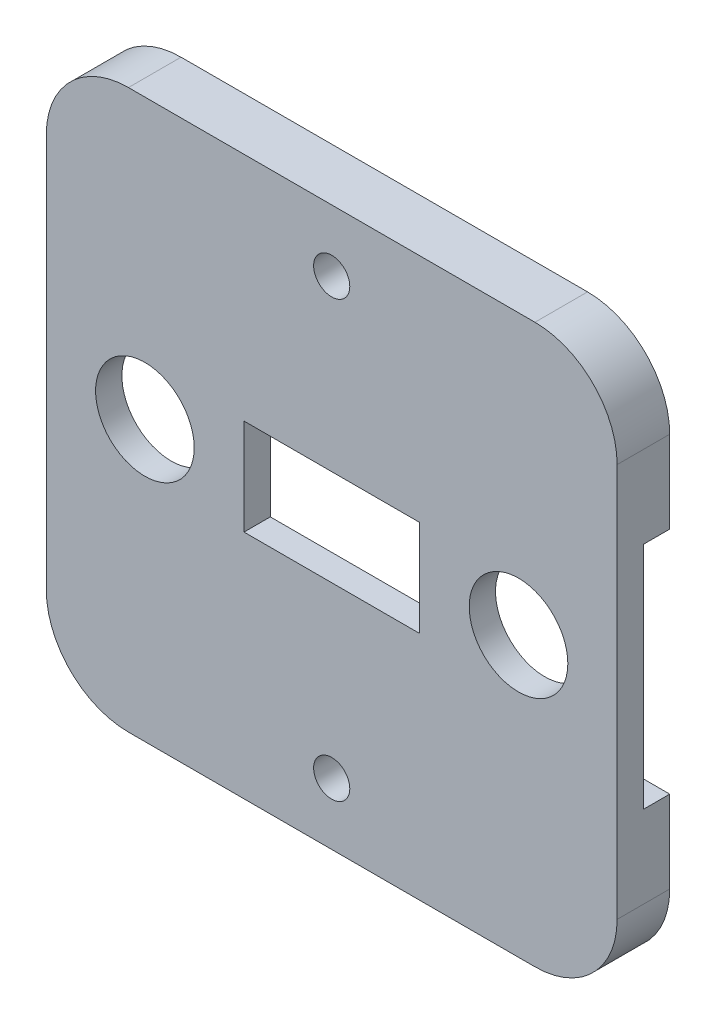
SolidWorks part; units mm, degrees
ref_plane "Front Plane" through (0, 0, 0) normal (0, 0, 1) x (1, 0, 0)
ref_plane "Top Plane" through (0, 0, 0) normal (0, 1, 0) x (1, 0, 0)
ref_plane "Right Plane" through (0, 0, 0) normal (1, 0, 0) x (0, 0, -1)
sketch "Sketch1" plane through (0, 0, 0) normal (0, 0, 1) x (1, 0, 0)
  line L1 (-22.0535, -18.6229) -> (-22.0535, -12.2729)
  line L2 (-15.7035, -5.9229) -> (15.7036, -5.9229)
  line L51 (-9.4424, -18.6229) -> (21.5953, -18.6229)
  line L52 (-22.0535, -18.6229) -> (22.0536, -18.6229) construction
  line L54 (-9.4424, -36.3521) -> (21.5953, -36.3521)
  line L55 (-22.0535, -36.3521) -> (22.0536, -36.3521) construction
  line L56 (-22.0535, -36.3521) -> (22.0536, -36.3521)
  line L57 (-22.0535, -36.3521) -> (-22.0535, -42.7021)
  line L58 (-15.7035, -49.0521) -> (15.7036, -49.0521)
  line L59 (22.0536, -36.3521) -> (22.0536, -42.7021)
  line L60 (22.0536, -18.6229) -> (-22.0535, -18.6229)
  line L61 (22.0536, -18.6229) -> (22.0536, -12.2729)
  circle A0 centre (-14.4335, -27.4875) radius 1.319 construction
  circle A1 centre (14.4336, -27.4875) radius 1.319 construction
  circle A2 centre (-14.4335, -27.4875) radius 1.319 construction
  circle A3 centre (14.4336, -27.4875) radius 1.319 construction
  arc A8 (-15.7035, -49.0521) -> (-22.0535, -42.7021) centre (-15.7035, -42.7021) cw
  arc A9 (15.7036, -49.0521) -> (22.0536, -42.7021) centre (15.7036, -42.7021) ccw
  arc A10 (15.7036, -5.9229) -> (22.0536, -12.2729) centre (15.7036, -12.2729) cw
  arc A11 (-22.0535, -12.2729) -> (-15.7035, -5.9229) centre (-15.7035, -12.2729) cw
  point P3 (-22.0535, -49.0521)
  point P21 (-22.0535, -49.0521)
  dimension "D6" = 7.62
  dimension "D4" = 6.35
  dimension "D3" = 12.7
  dimension "D5" = 7.62
  dimension "D1" = 0.508
  dimension "D2" = 0.508
extrude "Boss-Extrude1" add sketch "Sketch1" along normal offset from surface (4.064 mm away) 2.54 contours L60 L1 A11 L2 A10 L61 | L58 A9 L59 L56 L57 A8
sketch "Sketch2" plane through (0, 0, 4.064) normal (0, 0, 1) x (1, 0, 0)
  line L0 (-6.0134, -30.2624) -> (-6.0134, -30.4402) construction
  line L1 (-22.0535, -39.5271) -> (22.0536, -39.5271)
  line L7 (22.0536, -15.4479) -> (-22.0535, -15.4479)
  line L9 (-6.0134, -30.2624) -> (-6.0134, -24.7125) construction
  line L10 (-6.0134, -24.5347) -> (-6.0134, -24.7125) construction
  line L11 (6.0135, -24.5347) -> (-6.0134, -24.5347) construction
  line L12 (6.0135, -30.4402) -> (6.0135, -24.5347) construction
  line L13 (-6.0134, -30.4402) -> (6.0135, -30.4402) construction
  line L14 (-6.0134, -30.2624) -> (-6.0134, -30.4402) construction
  line L15 (-6.0134, -30.2624) -> (-6.0134, -24.7125) construction
  line L16 (-6.0134, -24.5347) -> (-6.0134, -24.7125) construction
  line L17 (6.0135, -24.5347) -> (-6.0134, -24.5347) construction
  line L18 (6.0135, -30.4402) -> (6.0135, -24.5347) construction
  line L19 (-6.0134, -30.4402) -> (6.0135, -30.4402) construction
  line L20 (-6.7754, -23.7727) -> (-6.7754, -24.7125)
  line L21 (-6.7754, -30.2624) -> (-6.7754, -24.7125)
  line L26 (-6.7754, -30.2624) -> (-6.7754, -31.2022)
  line L27 (-6.7754, -31.2022) -> (6.7755, -31.2022)
  line L30 (6.7755, -31.2022) -> (6.7755, -23.7727)
  line L31 (6.7755, -23.7727) -> (-6.7754, -23.7727)
  line L32 (22.0536, -18.6229) -> (-22.0535, -18.6229) construction
  line L33 (-22.0535, -15.4479) -> (-22.0535, -39.5271)
  line L35 (22.0536, -39.5271) -> (22.0536, -15.4479)
  circle A0 centre (-14.4335, -27.4875) radius 1.397 construction
  circle A1 centre (14.4336, -27.4875) radius 1.397 construction
  circle A2 centre (-14.4335, -27.4875) radius 1.397 construction
  circle A3 centre (14.4336, -27.4875) radius 1.397 construction
  circle A4 centre (14.4336, -27.4875) radius 3.81
  circle A5 centre (-14.4335, -27.4875) radius 3.81
  arc A10 (9.4933, -23.6775) -> (9.4933, -31.2975) centre (9.4933, -27.4875) ccw construction
  point P37 (-6.0134, -27.4875)
  point P45 (-22.0535, -27.4875)
  dimension "D3" = 0.762
  dimension "D5" = 7.62
  dimension "D1" = 7.62
  dimension "D4" = 3.175
extrude "Boss-Extrude2" add sketch "Sketch2" against normal offset from surface (2.032 mm away) 0.508
sketch "Sketch3" plane through (0, 0, 4.064) normal (0, 0, 1) x (1, 0, 0)
  line L0 (0, -49.0521) -> (0, -44.2896) construction
  line L1 (0, -10.6854) -> (0, -5.9229) construction
  line L2 (-15.7035, -49.0521) -> (15.7036, -49.0521) construction
  line L3 (-15.7035, -5.9229) -> (15.7036, -5.9229) construction
  line L6 (-15.7035, -49.0521) -> (15.7036, -49.0521) construction
  line L7 (-15.7035, -5.9229) -> (15.7036, -5.9229) construction
  point P12 (0, -44.2896)
  point P13 (0, -10.6854)
  point P14 (0, -10.6854)
  dimension "D1" = 4.7625
hole_wizard "#3 Clearance Hole1" positions "Sketch6" profile "Sketch7" hole size "#3" standard "ANSI Inch" end condition through all
sketch "Sketch6" plane through (0, 0, 4.064) normal (0, 0, 1) x (1, 0, 0)
  point P0 (0, -10.6854)
  point P3 (0, -44.2896)
sketch "Sketch7" plane through (0, -10.6854, 4.064) normal (1, 0, 0) x (0, -1, 0)
  line L0 (0, 0) -> (0, 4.064)
  line L1 (0, 4.064) -> (1.397, 4.064)
  line L2 (1.397, 4.064) -> (1.397, 0)
  line L5 (1.397, 0) -> (0, 0)
  line L11 (0, -6.35) -> (0, 107.95) construction
  dimension "Thru Hole Dia." = 2.794
  dimension "Thru Hole Depth" = 4.064
